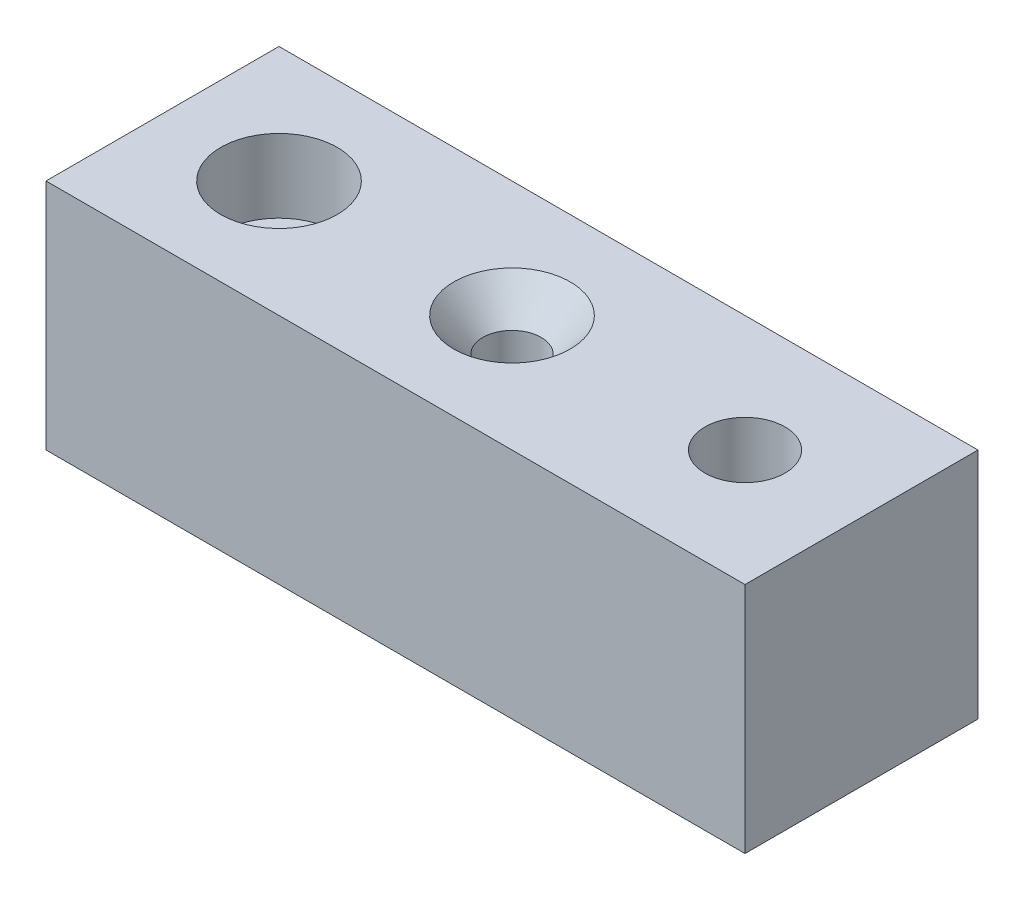
SolidWorks part; units mm, degrees
ref_plane "Front Plane" through (0, 0, 0) normal (0, 0, 1) x (1, 0, 0)
ref_plane "Top Plane" through (0, 0, 0) normal (0, 1, 0) x (1, 0, 0)
ref_plane "Right Plane" through (0, 0, 0) normal (1, 0, 0) x (0, 0, -1)
sketch "Sketch1" plane through (0, 0, 0) normal (0, 1, 0) x (1, 0, 0)
  line L1 (0, 0) -> (152.4, 0)
  line L2 (0, 0) -> (0, -50.8)
  line L3 (0, -50.8) -> (152.4, -50.8)
  line L4 (152.4, 0) -> (152.4, -50.8)
  dimension "D1" = 50.8
  dimension "D2" = 152.4
extrude "Boss-Extrude1" add sketch "Sketch1" along normal blind 50.8
hole_wizard "3/4-16 Tapped Hole1" positions "Sketch14" profile "Sketch15" tap size "3/4-16" standard "ANSI Inch"
sketch "Sketch14" plane through (0, 50.8, 0) normal (0, 1, 0) x (1, 0, 0)
  line L0 (0, 0) -> (0, -50.8) construction
  line L2 (0, -50.8) -> (152.4, -50.8) construction
  point P0 (127, -25.4)
  point P9 (138.1358, -50.8)
  dimension "D1" = 127
  dimension "D2" = 25.4
sketch "Sketch15" plane through (127, 50.8, 25.4) normal (1, 0, 0) x (0, 0, 1)
  line L0 (0, 0) -> (0, 43.3463)
  line L1 (0, 43.3463) -> (8.7312, 38.1)
  line L2 (8.7312, 38.1) -> (8.7312, 0)
  line L5 (8.7312, 0) -> (0, 0)
  line L10 (0, 43.3463) -> (-8.7313, 38.1) construction
  line L11 (0, -6.35) -> (0, 107.95) construction
  dimension "Tap Drill Dia." = 17.4625
  dimension "Tap Drill Depth" = 38.1
  dimension "Drill Angle" = 118
cosmetic thread "Hole Thread1" parameters "D1"=25.4, "D2"=19.05
hole_wizard "CBORE for #0 Binding Head Machine Screw2" positions "Sketch16" profile "Sketch17" counterbore size "#0" standard "ANSI Inch" end condition through all
sketch "Sketch16" plane through (0, 50.8, 0) normal (0, 1, 0) x (1, 0, 0)
  line L0 (0, 0) -> (0, -50.8) construction
  line L1 (0, -50.8) -> (152.4, -50.8) construction
  point P0 (25.4, -25.4)
  dimension "D1" = 25.4
  dimension "D2" = 25.4
sketch "Sketch17" plane through (25.4, 50.8, 25.4) normal (1, 0, 0) x (0, 0, 1)
  line L0 (0, 0) -> (0, 50.8)
  line L1 (0, 50.8) -> (8.001, 50.8)
  line L3 (8.001, 50.8) -> (8.001, 16.002)
  line L4 (8.001, 16.002) -> (12.7, 16.002)
  line L5 (12.7, 16.002) -> (12.7, 0)
  line L7 (12.7, 0) -> (0, 0)
  line L11 (0, -6.35) -> (0, 107.95) construction
  dimension "Thru Hole Dia." = 16.002
  dimension "Thru Hole Depth" = 50.8
  dimension "C'Bore Dia." = 25.4
  dimension "C'Bore Depth" = 16.002
hole_wizard "CSK for #0 Flat Head Machine Screw (100)3" positions "Sketch18" profile "Sketch19" countersink size "#0" standard "ANSI Inch" end condition through all
sketch "Sketch18" plane through (0, 50.8, 0) normal (0, 1, 0) x (1, 0, 0)
  line L0 (0, 0) -> (0, -50.8) construction
  line L2 (0, -50.8) -> (152.4, -50.8) construction
  point P0 (76.2, -25.4)
  dimension "D1" = 76.2
  dimension "D2" = 25.4
sketch "Sketch19" plane through (76.2, 50.8, 25.4) normal (1, 0, 0) x (0, 0, 1)
  line L0 (0, 0) -> (0, 50.8)
  line L1 (0, 50.8) -> (6.35, 50.8)
  line L2 (6.35, 50.8) -> (6.35, 7.3048)
  line L3 (6.35, 7.3048) -> (12.7, 0)
  line L5 (12.7, 0) -> (0, 0)
  line L6 (-6.35, 7.3048) -> (-12.7, 0) construction
  line L11 (0, -6.35) -> (0, 107.95) construction
  dimension "Thru Hole Dia." = 12.7
  dimension "Thru Hole Depth" = 50.8
  dimension "Near C'Sink Dia." = 25.4
  dimension "Near C'Sink Angle" = 82
